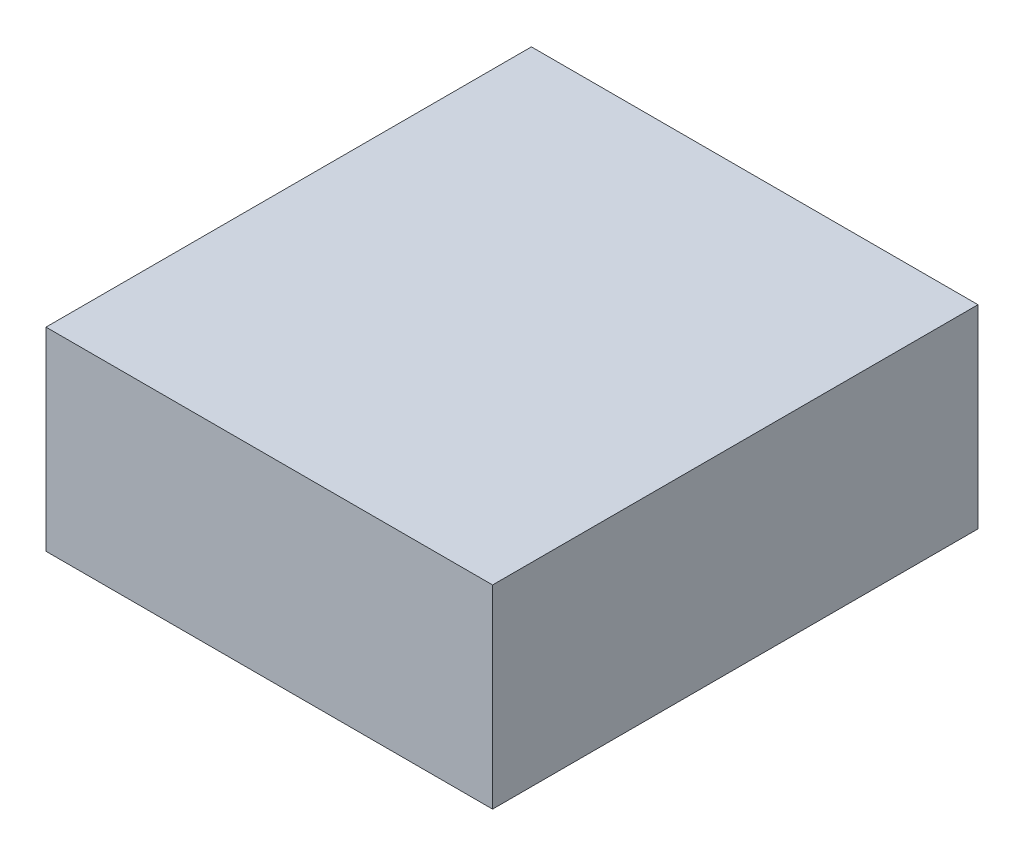
SolidWorks part; units mm, degrees
ref_plane "Front Plane" through (0, 0, 0) normal (0, 0, 1) x (1, 0, 0)
ref_plane "Top Plane" through (0, 0, 0) normal (0, 1, 0) x (1, 0, 0)
ref_plane "Right Plane" through (0, 0, 0) normal (1, 0, 0) x (0, 0, -1)
sketch "Sketch1" plane through (0, 0, 0) normal (0, 1, 0) x (1, 0, 0)
  line L1 (0, 0) -> (46, 0)
  line L2 (0, 0) -> (0, 50)
  line L3 (0, 50) -> (46, 50)
  line L4 (46, 0) -> (46, 50)
  dimension "D1" = 46
  dimension "D2" = 50
extrude "Boss-Extrude1" add sketch "Sketch1" along normal blind 20
